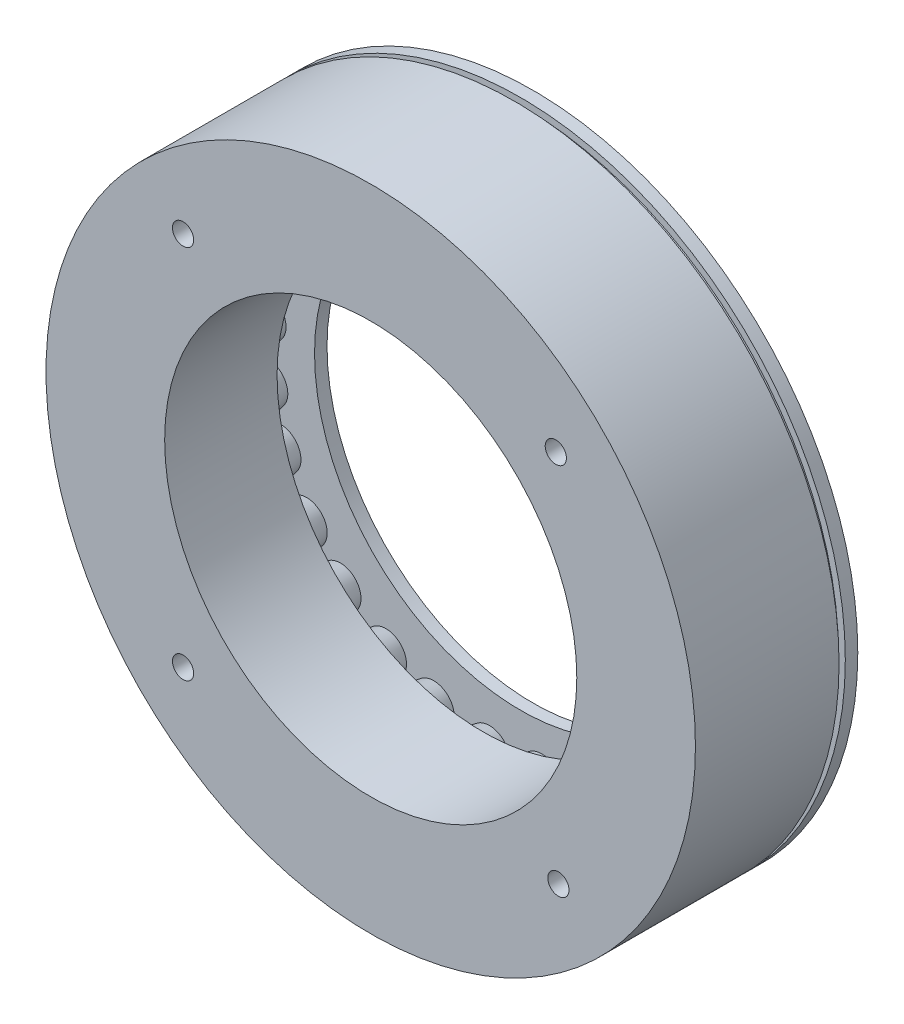
SolidWorks part; units mm, degrees
ref_plane "Alzado" through (0, 0, 0) normal (0, 0, 1) x (1, 0, 0)
ref_plane "Planta" through (0, 0, 0) normal (0, 1, 0) x (1, 0, 0)
ref_plane "Vista lateral" through (0, 0, 0) normal (1, 0, 0) x (0, 0, -1)
sketch "Croquis1" plane through (0, 0, 0) normal (0, 0, 1) x (1, 0, 0)
  circle A0 centre (0, 0) radius 52
  circle A1 centre (0, 0) radius 33
extrude "Saliente-Extruir1" add sketch "Croquis1" against normal blind 26
sketch "Croquis3" plane through (0, 0, 0) normal (0, 1, 0) x (1, 0, 0)
  line L0 (0, 34.84) -> (0, -7.8472) construction
  line L1 (-59.6876, 13.4964) -> (62.2935, 13.4964) construction
  line L6 (-24.8677, 24) -> (-24.8677, 18)
  line L7 (-50, 24) -> (-50, 18)
  line L8 (-50, 18) -> (-42.1823, 18)
  line L10 (-50, 24) -> (-24.8677, 24)
  line L11 (-24.8677, 18) -> (-42.1823, 18)
revolve "Cortar-Revolución5" cut sketch "Croquis3" angle 360 about L0
sketch "Croquis7" plane through (0, 0, -18) normal (0, 0, -1) x (-1, 0, 0)
  circle A0 centre (0, 0) radius 50
  circle A1 centre (0, 0) radius 35
  circle A2 centre (45.0351, 9.3722) radius 4
  circle A3 centre (38.855, 3.3601) radius 4
  circle A4 centre (45.9839, -1.2188) radius 4
  circle A5 centre (38.5753, -5.7397) radius 4
  circle A6 centre (32.2648, -21.9085) radius 4
  circle A7 centre (36.465, -13.8312) radius 4
  circle A8 centre (44.6417, -11.0959) radius 4
  circle A9 centre (40.9012, -21.0497) radius 4
  circle A10 centre (19.5639, -33.738) radius 4
  circle A11 centre (26.8528, -28.283) radius 4
  circle A12 centre (35.4064, -29.3664) radius 4
  circle A13 centre (27.7176, -36.7115) radius 4
  circle A14 centre (2.9881, -38.8854) radius 4
  circle A15 centre (11.9219, -37.1331) radius 4
  circle A16 centre (19.1585, -41.8205) radius 4
  circle A17 centre (9.0441, -45.1021) radius 4
  circle A18 centre (-14.1796, -36.331) radius 4
  circle A19 centre (-5.3701, -38.6285) radius 4
  circle A20 centre (-0.884, -45.9915) radius 4
  circle A21 centre (-11.4206, -44.5597) radius 4
  circle A22 centre (-28.5388, -26.5808) radius 4
  circle A23 centre (-21.5986, -32.4731) radius 4
  circle A24 centre (-20.7514, -41.0534) radius 4
  circle A25 centre (-29.6234, -35.1917) radius 4
  circle A26 centre (-37.2455, -11.5659) radius 4
  circle A27 centre (-33.5492, -19.8859) radius 4
  circle A28 centre (-36.5088, -27.9841) radius 4
  circle A29 centre (-41.9588, -18.8536) radius 4
  circle A30 centre (-38.5753, 5.7397) radius 4
  circle A31 centre (-38.855, -3.3601) radius 4
  circle A32 centre (-45.0351, -9.3722) radius 4
  circle A33 centre (-45.9839, 1.2188) radius 4
  circle A34 centre (-32.2648, 21.9085) radius 4
  circle A35 centre (-36.465, 13.8312) radius 4
  circle A36 centre (-44.6417, 11.0959) radius 4
  circle A37 centre (-40.9012, 21.0497) radius 4
  circle A38 centre (-19.5639, 33.738) radius 4
  circle A39 centre (-26.8528, 28.283) radius 4
  circle A40 centre (-35.4064, 29.3664) radius 4
  circle A41 centre (-27.7176, 36.7115) radius 4
  circle A42 centre (-2.9881, 38.8854) radius 4
  circle A43 centre (-11.9219, 37.1331) radius 4
  circle A44 centre (-19.1585, 41.8205) radius 4
  circle A45 centre (-9.0441, 45.1021) radius 4
  circle A46 centre (14.1796, 36.331) radius 4
  circle A47 centre (5.3701, 38.6285) radius 4
  circle A48 centre (0.884, 45.9915) radius 4
  circle A49 centre (11.4206, 44.5597) radius 4
  circle A50 centre (28.5388, 26.5808) radius 4
  circle A51 centre (21.5986, 32.4731) radius 4
  circle A52 centre (20.7514, 41.0534) radius 4
  circle A53 centre (29.6234, 35.1917) radius 4
  circle A54 centre (37.2455, 11.5659) radius 4
  circle A55 centre (33.5492, 19.8859) radius 4
  circle A56 centre (36.5088, 27.9841) radius 4
  circle A57 centre (41.9588, 18.8536) radius 4
  point P119 (0, 0)
  dimension "D1" = 14
extrude "Saliente-Extruir3" add sketch "Croquis7" along normal blind 4 draft 10 contours A35 | A37 | A34 | A39 | A40 | A33 | A32 | A26 | A29 | A28 | A27 | A22 | A25 | A23 | A24 | A18 | A21 | A19 | A20 | A14 | A17 | A15 | A16 | A13 | A11 | A9 | A6 | A7 | A8 | A12 | A5 | A4 | A3 | A2 | A54 | A57 | A55 | A56 | A50 | A53 | A51 | A52 | A46 | A49 | A47 | A48 | A45 | A42 | A43 | A44 | A41 | A38 | A30 | A36 | A31 | A10
sketch "Croquis8" plane through (0, 0, 0) normal (0, 1, 0) x (1, 0, 0)
  line L0 (52, 26) -> (-52, 26) construction
  line L1 (-64.453, 24) -> (-50.9229, 24)
  line L2 (-64.453, 24) -> (-64.453, 23)
  line L3 (-64.453, 23) -> (-50.9229, 23)
  line L4 (-50.9229, 24) -> (-50.9229, 23)
  line L5 (-64.453, 24) -> (-50.9229, 23) construction
  line L6 (-64.453, 23) -> (-50.9229, 24) construction
  point P0 (-57.688, 23.5)
  dimension "D1" = 1
  dimension "D2" = 2
revolve "Cortar-Revolución6" cut sketch "Croquis8" angle 360 about L0
sketch "Croquis10" plane through (0, 0, 0) normal (0, 0, 1) x (1, 0, 0)
  line L2 (-30.052, -30.052) -> (-21.4775, -21.4775) construction
  line L4 (30.052, -30.052) -> (21.4775, -21.4775) construction
  line L8 (-30.052, 30.052) -> (-21.4775, 21.4775) construction
  line L9 (30.052, 30.052) -> (21.4775, 21.4775) construction
  line L10 (-24.8677, 0) -> (-42.1823, 0) construction
  line L11 (-59.6876, 0) -> (62.2935, 0) construction
  point P4 (30.052, -30.052)
  point P19 (0, 0)
  point P20 (-30.052, -30.052)
  point P22 (-30.052, 30.052)
  point P24 (30.052, 30.052)
  point P26 (0, 0)
  dimension "D2" = 4
hole_wizard "Taladro de margen para M31" positions "Croquis3D1" profile "Croquis16" hole size "M3" standard "ISO"
sketch3d "Croquis3D1"
  line L0 (30.052, 30.052, 0) -> (21.4775, 21.4775, 0) construction
  point P0 (-30.052, -30.052, 0)
  point P3 (30.052, -30.052, 0)
  point P6 (29.6396, 29.6396, 0)
  point P10 (-30.052, 30.052, 0)
sketch "Croquis16" plane through (-30.052, -30.052, 0) normal (1, 0, 0) x (0, -1, 0)
  line L0 (0, 0) -> (0, 10)
  line L1 (0, 10) -> (1.7, 8.9785)
  line L2 (1.7, 8.9785) -> (1.7, 0)
  line L5 (1.7, 0) -> (0, 0)
  line L10 (0, 10) -> (-1.7, 8.9785) construction
  line L11 (0, -6.35) -> (0, 107.95) construction
  dimension "Diámetro de taladro" = 3.4
  dimension "Profundidad de taladro" = 10
  dimension "Ángulo de perforador" = 118
